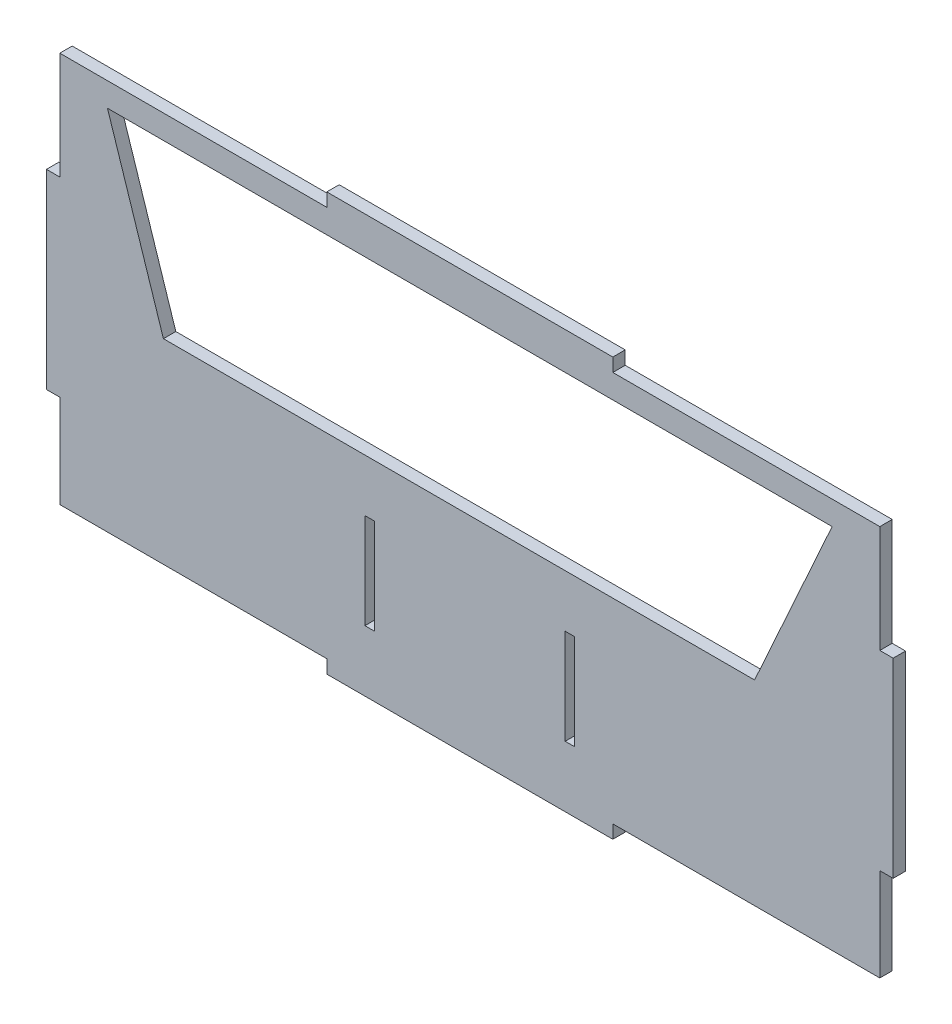
SolidWorks part; units mm, degrees
ref_plane "Front Plane" through (0, 0, 0) normal (0, 0, 1) x (1, 0, 0)
ref_plane "Top Plane" through (0, 0, 0) normal (0, 1, 0) x (1, 0, 0)
ref_plane "Right Plane" through (0, 0, 0) normal (1, 0, 0) x (0, 0, -1)
sketch "Sketch1" plane through (0, 0, 0) normal (0, 0, 1) x (1, 0, 0)
  line L0 (-38, 18) -> (38, 18)
  line L1 (-43, -20.5) -> (43, -20.5)
  line L2 (-43, -20.5) -> (-43, 20.5)
  line L3 (-43, 20.5) -> (43, 20.5)
  line L4 (43, -20.5) -> (43, 20.5)
  line L5 (-43, -20.5) -> (43, 20.5) construction
  line L6 (-43, 20.5) -> (43, -20.5) construction
  line L7 (38, 18) -> (29.8671, 0)
  line L8 (55, 0) -> (-55, 0) construction
  line L9 (29.8671, 0) -> (-32.1329, 0)
  line L10 (-32.1329, 0) -> (-38, 18)
  line L11 (0, -55) -> (0, 55) construction
  point P0 (0, 0)
  dimension "D1" = 86
  dimension "D2" = 41
  dimension "D3" = 76
  dimension "D4" = 62
  dimension "D5" = 38
  dimension "D6" = 18
extrude "Boss-Extrude1" add sketch "Sketch1" along normal blind 1.3
sketch "Sketch2" plane through (0, 0, 1.3) normal (0, 0, 1) x (1, 0, 0)
  line L0 (-43, 20.5) -> (-43, -20.5) construction
  line L1 (-43, 9.25) -> (-44.4, 9.25)
  line L2 (-43, 9.25) -> (-43, -10.75)
  line L3 (-43, -10.75) -> (-44.4, -10.75)
  line L4 (-44.4, 9.25) -> (-44.4, -10.75)
  line L5 (43, -20.5) -> (43, 20.5) construction
  line L6 (43, 9.25) -> (44.4, 9.25)
  line L7 (43, 9.25) -> (43, -10.75)
  line L8 (43, -10.75) -> (44.4, -10.75)
  line L9 (44.4, 9.25) -> (44.4, -10.75)
  line L10 (43, 20.5) -> (-43, 20.5) construction
  line L11 (-15, 20.5) -> (15, 20.5)
  line L12 (-15, 20.5) -> (-15, 21.9)
  line L13 (-15, 21.9) -> (15, 21.9)
  line L14 (15, 20.5) -> (15, 21.9)
  line L15 (-43, -20.5) -> (43, -20.5) construction
  line L16 (-15, -20.5) -> (15, -20.5)
  line L17 (-15, -20.5) -> (-15, -21.9)
  line L18 (-15, -21.9) -> (15, -21.9)
  line L19 (15, -20.5) -> (15, -21.9)
  line L20 (0, -55) -> (0, 55) construction
  dimension "D1" = 1.4
  dimension "D2" = 1.4
  dimension "D3" = 1.4
  dimension "D4" = 1.4
  dimension "D5" = 30
  dimension "D6" = 30
  dimension "D7" = 20
  dimension "D8" = 20
  dimension "D9" = 15
  dimension "D10" = 15
  dimension "D11" = 9.75
  dimension "D12" = 9.75
extrude "Boss-Extrude2" add sketch "Sketch2" against normal blind 1.3
sketch "Sketch3" plane through (0, 0, 1.3) normal (0, 0, 1) x (1, 0, 0)
  line L0 (0, -55) -> (0, 55) construction
  line L1 (-11, -5.5) -> (-10, -5.5)
  line L2 (-11, -5.5) -> (-11, -15.5)
  line L3 (-11, -15.5) -> (-10, -15.5)
  line L4 (-10, -5.5) -> (-10, -15.5)
  line L5 (10, -5.5) -> (11, -5.5)
  line L6 (10, -5.5) -> (10, -15.5)
  line L7 (10, -15.5) -> (11, -15.5)
  line L8 (11, -5.5) -> (11, -15.5)
  line L9 (-43, -20.5) -> (-15, -20.5) construction
  line L10 (15, -20.5) -> (43, -20.5) construction
  dimension "D1" = 10
  dimension "D2" = 10
  dimension "D3" = 1
  dimension "D4" = 1
  dimension "D5" = 10
  dimension "D6" = 10
  dimension "D7" = 5
  dimension "D8" = 5
extrude "Cut-Extrude1" cut sketch "Sketch3" against normal through all
